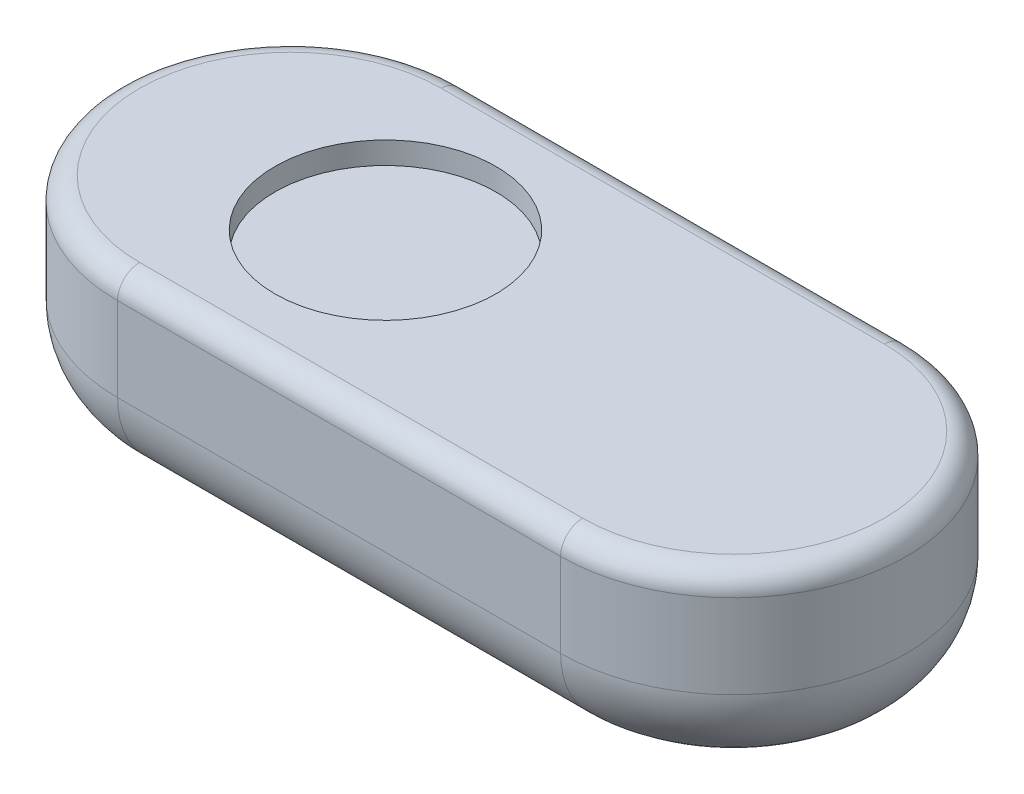
SolidWorks part; units mm, degrees
ref_plane "前基準面" through (0, 0, 0) normal (0, 0, 1) x (1, 0, 0)
ref_plane "上基準面" through (0, 0, 0) normal (0, 1, 0) x (1, 0, 0)
ref_plane "右基準面" through (0, 0, 0) normal (1, 0, 0) x (0, 0, -1)
sketch "草圖1" plane through (0, 0, 0) normal (0, 1, 0) x (1, 0, 0)
  line L0 (-20.05, 0) -> (20.05, 0) construction
  line L1 (-20.05, 15.65) -> (20.05, 15.65)
  line L2 (-20.05, -15.65) -> (20.05, -15.65)
  line L3 (-35.7, 0) -> (35.7, 0) construction
  arc A0 (-20.05, 15.65) -> (-20.05, -15.65) centre (-20.05, 0) ccw
  arc A1 (20.05, -15.65) -> (20.05, 15.65) centre (20.05, 0) ccw
  point P2 (0, 0)
  dimension "D1" = 31.3
  dimension "D2" = 71.4
extrude "填料-伸長1" add sketch "草圖1" along normal blind 17.6 contours L1 A1 L2 A0
fillet "圓角2" radius 2 4 edges at (-35.7, 17.6, 0) (0, 17.6, 15.65) (35.7, 17.6, 0) (0, 17.6, -15.65)
fillet "圓角3" radius 8 4 edges at (0, 0, 15.65) (35.7, 0, 0) (0, 0, -15.65) (-35.7, 0, 0)
sketch "草圖2" plane through (0, 17.6, 0) normal (0, 1, 0) x (1, 0, 0)
  circle A0 centre (-11.4554, 0) radius 10
  dimension "D1" = 20
extrude "除料-伸長1" cut sketch "草圖2" against normal blind 2
